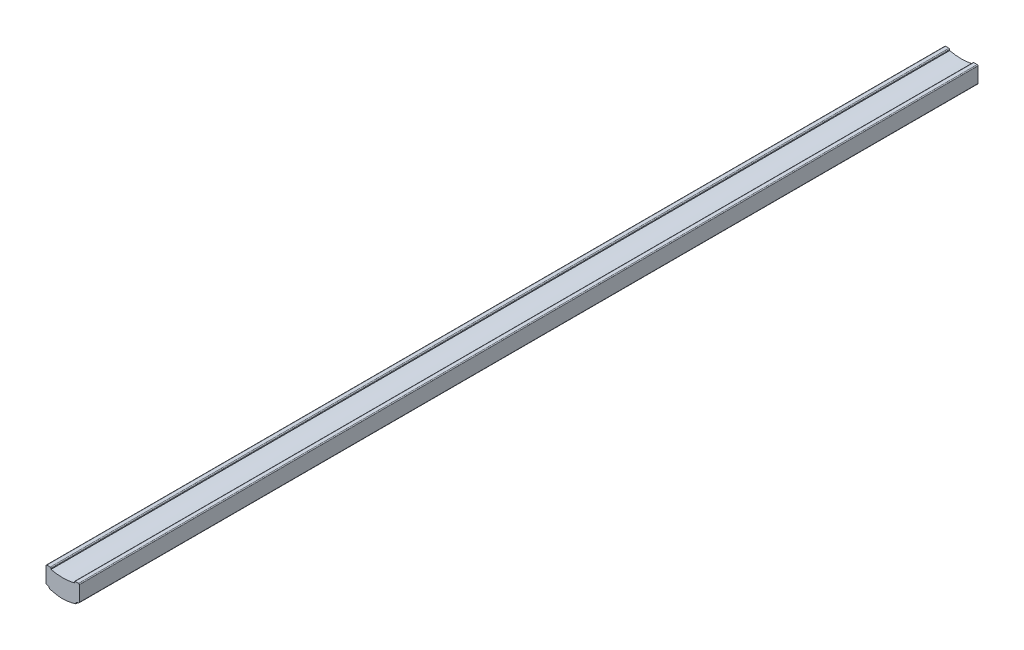
SolidWorks part; units mm, degrees
ref_plane "Alzado" through (0, 0, 0) normal (0, 0, 1) x (1, 0, 0)
ref_plane "Planta" through (0, 0, 0) normal (0, 1, 0) x (1, 0, 0)
ref_plane "Vista lateral" through (0, 0, 0) normal (1, 0, 0) x (0, 0, -1)
sketch "Croquis1" plane through (0, 0, 0) normal (0, 0, 1) x (1, 0, 0)
  line L0 (-13.731, 11.1484) -> (-13.731, 2.0357)
  line L1 (-13.231, 11.6484) -> (-11.231, 11.6484)
  line L2 (-10.731, 11.1484) -> (-10.731, 10.6484)
  line L8 (-13.3561, 1.5516) -> (-12.1695, 1.2449)
  line L9 (-11.7946, 0.7608) -> (-11.7946, 0.4429)
  line L13 (-10.0124, 1.7815) -> (-10.0124, 1.7815)
  line L14 (-11.731, 3.1973) -> (-11.6691, 3.1813)
  line L15 (-11.731, 8.8365) -> (-11.731, 3.1973)
  line L16 (-11.731, 8.8365) -> (-11.731, 8.8365)
  line L17 (-11.731, 8.8365) -> (-11.731, 8.8365)
  line L18 (5.769, 11.6484) -> (3.769, 11.6484)
  line L19 (3.269, 11.1484) -> (3.269, 10.6484)
  line L20 (6.269, 11.1484) -> (6.269, 2.0357)
  line L21 (5.8941, 1.5516) -> (4.7075, 1.2449)
  line L22 (4.3327, 0.7608) -> (4.3327, 0.4429)
  line L23 (4.269, 8.8365) -> (4.269, 3.1973)
  arc A0 (-10.731, 10.6484) -> (-3.731, 9.8203) centre (-3.731, 39.8203) ccw
  arc A1 (-3.731, -1.1797) -> (-11.5837, 0.1565) centre (-2.6698, 28.8016) cw
  arc A2 (-11.7946, 0.7608) -> (-12.1695, 1.2449) centre (-12.2946, 0.7608) ccw
  arc A3 (-11.231, 11.6484) -> (-10.731, 11.1484) centre (-11.231, 11.1484) cw
  arc A4 (-13.731, 11.1484) -> (-13.231, 11.6484) centre (-13.231, 11.1484) cw
  arc A5 (-13.3561, 1.5516) -> (-13.731, 2.0357) centre (-13.231, 2.0357) cw
  arc A6 (-11.5837, 0.1565) -> (-11.7946, 0.4429) centre (-11.4946, 0.4429) cw
  arc A7 (-3.6602, 0.8191) -> (-10.0124, 1.7815) centre (-2.6698, 28.8016) cw
  arc A8 (-10.0124, 1.7815) -> (-10.0124, 1.7815) centre (-10.0124, 1.7815) cw
  arc A9 (-10.0124, 1.7815) -> (-11.6691, 3.1813) centre (-12.2946, 0.7608) ccw
  arc A10 (-11.731, 3.1973) -> (-11.731, 3.1973) centre (-11.731, 3.1973) cw
  arc A11 (-11.731, 8.8365) -> (-11.731, 8.8365) centre (-11.731, 8.8365) cw
  arc A12 (-11.731, 8.8365) -> (-11.731, 8.8365) centre (-11.731, 8.8365) cw
  arc A13 (-11.731, 8.8365) -> (-3.731, 7.8203) centre (-3.731, 39.8203) ccw
  arc A14 (6.269, 11.1484) -> (5.769, 11.6484) centre (5.769, 11.1484) ccw
  arc A15 (3.769, 11.6484) -> (3.269, 11.1484) centre (3.769, 11.1484) ccw
  arc A16 (5.8941, 1.5516) -> (6.269, 2.0357) centre (5.769, 2.0357) ccw
  arc A17 (4.3327, 0.7608) -> (4.7075, 1.2449) centre (4.8327, 0.7608) cw
  arc A18 (4.1218, 0.1565) -> (4.3327, 0.4429) centre (4.0327, 0.4429) ccw
  arc A19 (-3.731, -1.1797) -> (4.1218, 0.1565) centre (-4.7921, 28.8016) ccw
  arc A20 (-3.8017, 0.8191) -> (2.5505, 1.7815) centre (-4.7921, 28.8016) ccw
  arc A21 (2.5505, 1.7815) -> (4.2071, 3.1813) centre (4.8327, 0.7608) cw
  arc A22 (4.269, 8.8365) -> (-3.731, 7.8203) centre (-3.731, 39.8203) cw
  arc A23 (3.269, 10.6484) -> (-3.731, 9.8203) centre (-3.731, 39.8203) cw
  point P14 (-11.7946, 1.148)
  point P20 (-10.731, 11.6484)
  point P23 (-13.731, 11.6484)
  point P26 (-13.731, 1.6484)
  dimension "D4" = 30
  dimension "D6" = 1
  dimension "D8" = 30
  dimension "D5" = 0.5
  dimension "D7" = 0.5
  dimension "D10" = 0.5
  dimension "D11" = 0.5
  dimension "D12" = 0.3
  dimension "D1" = 10
  dimension "D2" = 3
  dimension "D3" = 11
  dimension "D9" = 2
  dimension "D13" = 2
extrude "Saliente-Extruir1" add sketch "Croquis1" along normal blind 540
